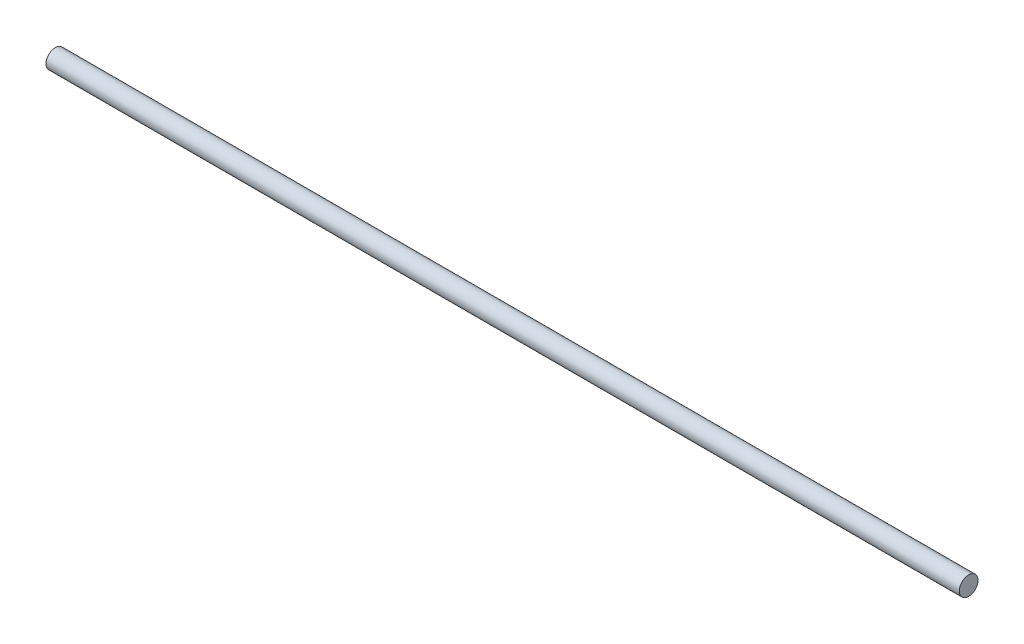
SolidWorks part; units mm, degrees
ref_plane "Front Plane" through (0, 0, 0) normal (0, 0, 1) x (1, 0, 0)
ref_plane "Top Plane" through (0, 0, 0) normal (0, 1, 0) x (1, 0, 0)
ref_plane "Right Plane" through (0, 0, 0) normal (1, 0, 0) x (0, 0, -1)
sketch "Sketch1" plane through (0, 0, 0) normal (1, 0, 0) x (0, 0, -1)
  circle A0 centre (0, 0) radius 4
  dimension "D1" = 8
extrude "Boss-Extrude1" add sketch "Sketch1" along normal blind 390
equation "\"X-ROD-SPACING\"=45"
equation "\"Y-ROD-SPACING\"=75"
equation "\"Z-ROD-SPACING\"=17.5"
equation "\"Y-BED-OFFSET\"=2"
equation "\"Y-BED-ROD-INSET\"=3.5"
equation "\"T-SLOT-NUT-FILLET-RADIUS\"=0.25"
equation "\"T-SLOT-SCREW-SHAFT-RADIUS\"=1.75"
equation "\"T-SLOT-SCREW-SHAFT-CUTOUT-LENGTH\"=10.5"
equation "\"T-SLOT-NUT-DEPTH\"=4.2"
equation "\"T-SLOT-NUT-WIDTH\"=3"
equation "\"T-SLOT-NUT-END-DISTANCE\"=8"
equation "\"ACRYLIC-THICKNESS\"=10"
equation "\"ACRYLIC-THICKNESS2\"=4.5"
equation "\"ACRYLIC-TAB-CUTOUT-SIZE\"=\"ACRYLIC-THICKNESS\"+\"ACRYLIC-TAB-TOLERANCE\"*2"
equation "\"ACRYLIC-TAB-WIDTH\"=\"ACRYLIC-THICKNESS\""
equation "\"ACRYLIC-M3-HOLE\"=3.2"
equation "\"SMOOTHROD-CAP-SCREW-DISTANCE\"=20"
equation "\"FRAME-WIDTH-INNER\"=370"
equation "\"NEMA17-HOLE-SPACING\"=31"
equation "\"NEMA17-CENTRAL-CUTOUT\"=22.5"
equation "\"Z-BRACKET-REACH\"=55"
equation "\"Z-ROD-INSET\"=16"
equation "\"TOP-BRACKET-SPACING\"=40"
equation "\"SMOOTHROD-X-LENGTH\"=350"
equation "\"SMOOTHROD-Y-LENGTH\"=350"
equation "\"SMOOTHROD-Z-LENGTH\"=350"
equation "\"SMOOTHROD-TIGHTENING-HEADROOM\"=1"
equation "\"LEADSCREW-Z-LENGTH\"=300"
equation "\"SCREW-LENGTH-FRAME\"=\"ACRYLIC-THICKNESS\" + 10"
equation "\"SCREW-HEAD-RADIUS\"=6"
equation "\"PRINTED-X-SMOOTHROD-DIAMETER\"=8.2"
equation "\"PRINTED-X-SMOOTHROD-CUTOUT\"=10"
equation "\"PRINTED-X-BASE-HEIGHT\"=10"
equation "\"PRINTED-LM8UU-CUTOUT-SIZE\"=16"
equation "\"PRINTED-LM8UU-CUTOUT-LENGTH\"=24.5"
equation "\"PRINTED-X-IDLER-HEIGHT\"=16"
equation "\"PSU-MOUNTING-WIDTH\"=95"
equation "\"PSU-MOUNTING-HEIGHT\"=177"
equation "\"Y-BELT-TO-ROD-DISTANCE\"=20"
equation "\"SPOOL-HOLDER-ROD-SPACING\"=150"
equation "\"D1@Boss-Extrude1\"=\"FRAME-WIDTH-INNER\"+\"ACRYLIC-THICKNESS\"*2"
